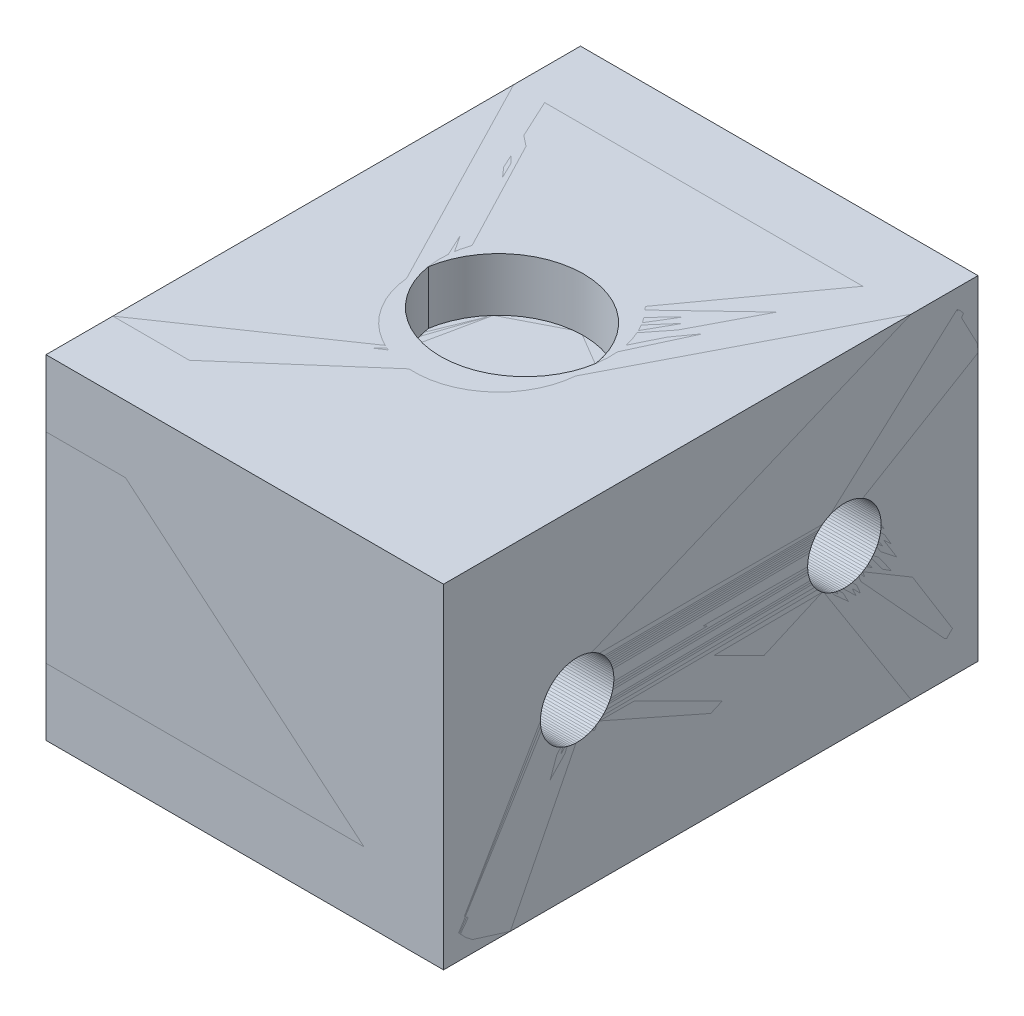
SolidWorks part; units mm, degrees
other "Symétrie_D"
ref_plane "Plan de face" through (0, 0, 0) normal (0, 0, 1) x (1, 0, 0)
ref_plane "Plan de dessus" through (0, 0, 0) normal (0, 1, 0) x (1, 0, 0)
ref_plane "Plan de droite" through (0, 0, 0) normal (1, 0, 0) x (0, 0, -1)
sketch "Esquisse2" plane through (0, 0, 0) normal (0, 0, 1) x (1, 0, 0)
  line L1 (0, 100) -> (-29.75, 100)
  line L2 (0, 100) -> (0, 75)
  line L3 (0, 75) -> (-29.75, 75)
  line L4 (-29.75, 100) -> (-29.75, 75)
  line L5 (0, 95) -> (0, -95) construction
  line L6 (3.175, 100) -> (0, 100) construction
  dimension "D1" = 29.75
  dimension "D2" = 25
extrude "Boss.-Extru.1" add sketch "Esquisse2" against normal blind 40
sketch "Esquisse3" plane through (0, 100, 0) normal (0, 1, 0) x (1, 0, 0)
  line L1 (0, 40) -> (-29.75, 40) construction
  line L3 (-29.75, 40) -> (-29.75, 0) construction
  circle A0 centre (-14.875, 21) radius 6.35
  dimension "D1" = 12.7
  dimension "D2" = 19
  dimension "D3" = 14.875
extrude "Enlèv. mat.-Extru.1" cut sketch "Esquisse3" against normal blind 4
hole_wizard "Dégagement M51" positions "Esquisse3D1" profile "Esquisse5" hole size "M5" standard "Ansi Metric" end condition through all
sketch3d "Esquisse3D1"
  line L0 (0, 75, 0) -> (0, 100, 0) construction
  point P0 (0, 87.5, -10)
  point P2 (0, 87.5, -30)
  point P8 (0, 87.5, 0)
  dimension "D1" = 20
  dimension "D2" = 10
sketch "Esquisse5" plane through (0, 87.5, -10) normal (0, 1, 0) x (0, 0, -1)
  line L0 (0, 0) -> (0, 29.75)
  line L1 (0, 29.75) -> (2.75, 29.75)
  line L2 (2.75, 29.75) -> (2.75, 0)
  line L5 (2.75, 0) -> (0, 0)
  line L11 (0, -6.35) -> (0, 107.95) construction
  dimension "Diamètre du perçage jusqu'au prochain" = 5.5
  dimension "Profondeur du perçage jusqu'au prochain" = 29.75
ref_plane "Plan1" through (0, 0, -20) normal (0, 0, 1) x (1, 0, 0)
fillet "Congé1" radius 5 2 edges at (-14.875, 100, 0) (-14.875, 75, 0)
mirror "Symétrie1" about plane through (0, 0, -20) normal (0, 0, 1) of bodies 103
